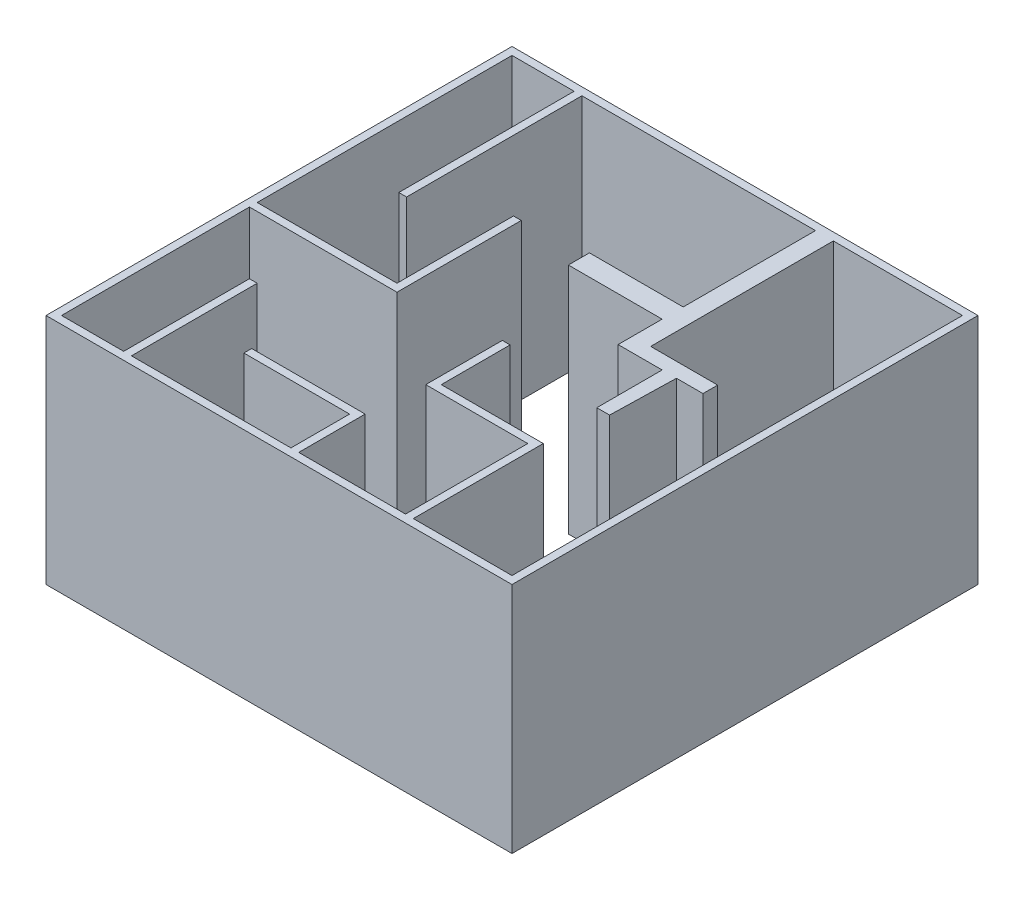
SolidWorks part; units mm, degrees
ref_plane "Front Plane" through (0, 0, 0) normal (0, 0, 1) x (1, 0, 0)
ref_plane "Top Plane" through (0, 0, 0) normal (0, 1, 0) x (1, 0, 0)
ref_plane "Right Plane" through (0, 0, 0) normal (1, 0, 0) x (0, 0, -1)
sketch "Sketch1" plane through (0, 0, 0) normal (0, 1, 0) x (1, 0, 0)
  line L0 (500, 13096.7551) -> (9500, 13096.7551)
  line L1 (0, 0) -> (30000, 0)
  line L2 (0, 0) -> (0, 30000)
  line L3 (0, 30000) -> (30000, 30000)
  line L4 (30000, 0) -> (30000, 30000)
  line L5 (500, 500) -> (4500, 500)
  line L6 (500, 500) -> (500, 12596.7551)
  line L7 (500, 29500) -> (4500, 29500)
  line L8 (29500, 500) -> (29500, 29500)
  line L9 (9500, 13096.7551) -> (9500, 20596.7551)
  line L10 (9500, 20596.7551) -> (10000, 20596.7551)
  line L11 (10000, 20596.7551) -> (10000, 12596.7551)
  line L12 (10000, 12596.7551) -> (500, 12596.7551)
  line L13 (4500, 500) -> (4500, 8596.7551)
  line L14 (4500, 8596.7551) -> (5000, 8596.7551)
  line L15 (5000, 8596.7551) -> (5000, 500)
  line L16 (500, 13096.7551) -> (500, 29500)
  line L17 (5000, 500) -> (15269.1839, 500)
  line L18 (8462.0118, 4776.7457) -> (15769.1839, 4776.7457)
  line L19 (15769.1839, 4776.7457) -> (15769.1839, 500)
  line L20 (8462.0118, 4776.7457) -> (8462.0118, 4276.7457)
  line L21 (8462.0118, 4276.7457) -> (15269.1839, 4276.7457)
  line L22 (15269.1839, 4276.7457) -> (15269.1839, 500)
  line L23 (4500, 18212.4546) -> (4500, 29500)
  line L24 (4500, 18212.4546) -> (5000, 18212.4546)
  line L25 (5000, 18212.4546) -> (5000, 29500)
  line L26 (5000, 29500) -> (20037.0639, 29500)
  line L27 (15769.1839, 500) -> (22646.6038, 500)
  line L28 (20037.0639, 29500) -> (20037.0639, 20983.6804)
  line L29 (20037.0639, 16794.6973) -> (22870.781, 16794.6973)
  line L30 (25500, 16794.6973) -> (25500, 17739.272)
  line L31 (25500, 17739.272) -> (21187.4624, 17739.272)
  line L32 (21187.4624, 17739.272) -> (21187.4624, 29500)
  line L33 (20037.0639, 20983.6804) -> (14000, 20983.6804)
  line L34 (14000, 20983.6804) -> (14000, 19628.4212)
  line L35 (14000, 19628.4212) -> (20037.0639, 19628.4212)
  line L36 (16579.4018, 13298.6717) -> (16579.4018, 8868.4685)
  line L37 (16579.4018, 8868.4685) -> (23146.6038, 8868.4685)
  line L38 (23146.6038, 8868.4685) -> (23146.6038, 500)
  line L40 (22646.6038, 500) -> (22646.6038, 8368.4685)
  line L41 (22646.6038, 8368.4685) -> (16079.4018, 8368.4685)
  line L42 (16079.4018, 8368.4685) -> (16079.4018, 13298.6717)
  line L43 (16079.4018, 13298.6717) -> (16579.4018, 13298.6717)
  line L44 (22870.781, 16794.6973) -> (22870.781, 12587.6548)
  line L45 (22870.781, 12587.6548) -> (23694.0368, 12587.6548)
  line L46 (23694.0368, 12587.6548) -> (23794.8281, 16794.6973)
  line L47 (20037.0639, 19628.4212) -> (20037.0639, 16794.6973)
  line L48 (23794.8281, 16794.6973) -> (25500, 16794.6973)
  line L49 (21187.4624, 29500) -> (29500, 29500)
  line L50 (23146.6038, 500) -> (29500, 500)
  point P51 (0, 0)
  point P52 (22448.0082, 500)
  point P53 (23146.6038, 500)
  dimension "D1" = 500
  dimension "D2" = 30000
  dimension "D3" = 30000
  dimension "D4" = 500
  dimension "D5" = 500
  dimension "D6" = 500
  dimension "D7" = 500
  dimension "D8" = 500
  dimension "D9" = 4000
  dimension "D10" = 500
  dimension "D11" = 4000
  dimension "D12" = 4000
  dimension "D13" = 500
  dimension "D14" = 9000
  dimension "D15" = 8000
  dimension "D16" = 500
  dimension "D17" = 500
  dimension "D18" = 500
  dimension "D19" = 500
  dimension "D20" = 500
  dimension "D22" = 4000
  dimension "D23" = 4000
extrude "Boss-Extrude1" add sketch "Sketch1" along normal blind 15000
